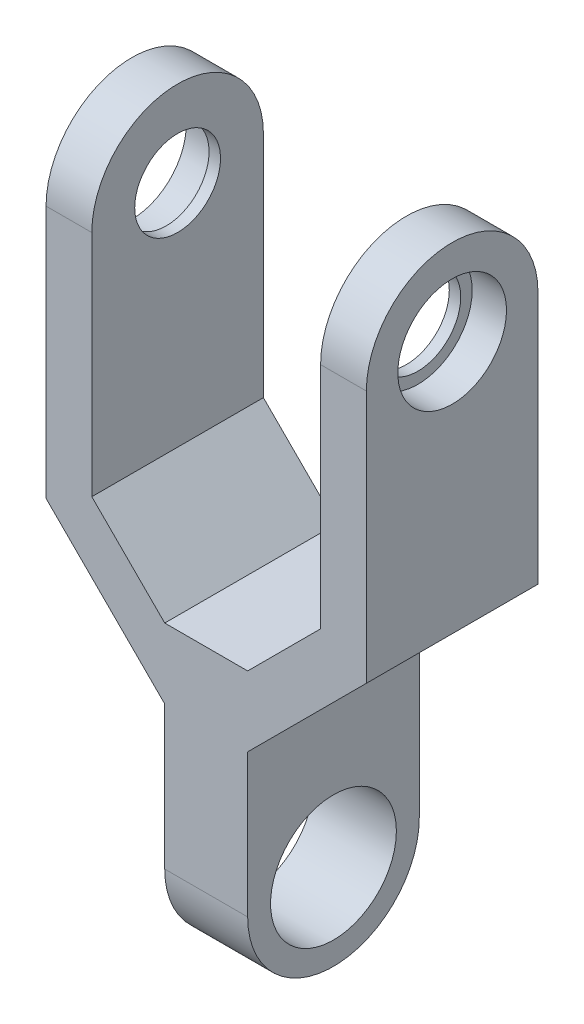
SolidWorks part; units mm, degrees
ref_plane "前视基准面" through (0, 0, 0) normal (0, 0, 1) x (1, 0, 0)
ref_plane "上视基准面" through (0, 0, 0) normal (0, 1, 0) x (1, 0, 0)
ref_plane "右视基准面" through (0, 0, 0) normal (1, 0, 0) x (0, 0, -1)
sketch "草图1" plane through (0, 0, 0) normal (0, 0, 1) x (1, 0, 0)
  line L0 (0, 0) -> (14.5, 0)
  line L1 (14.5, 0) -> (14.5, 25)
  line L2 (14.5, 25) -> (35.25, 45.75)
  line L3 (35.25, 45.75) -> (35.25, 90)
  line L4 (35.25, 90) -> (27.25, 90)
  line L5 (27.25, 90) -> (27.25, 50)
  line L6 (27.25, 50) -> (-12.75, 50)
  line L7 (-12.75, 50) -> (-12.75, 90)
  line L8 (-12.75, 90) -> (-20.75, 90)
  line L9 (-20.75, 90) -> (-20.75, 45.75)
  line L11 (0, 25) -> (0, 0)
  line L12 (0, 25) -> (-20.75, 45.75)
  line L13 (7.25, 0) -> (7.25, 35.1674) construction
  dimension "D1" = 135
  dimension "D2" = 135
  dimension "D3" = 14.5
  dimension "D4" = 8
  dimension "D5" = 8
  dimension "D6" = 40
  dimension "D7" = 90
  dimension "D8" = 25
  dimension "D9" = 40
extrude "凸台-拉伸1" add sketch "草图1" along normal blind 30
sketch "草图2" plane through (0, 0, 30) normal (0, 0, 1) x (1, 0, 0)
  line L0 (-12.75, 50) -> (0, 37.25)
  line L1 (0, 37.25) -> (14.5, 37.25)
  line L2 (14.5, 37.25) -> (27.25, 50)
  line L3 (-20.75, 45.75) -> (0, 25) construction
  line L4 (14.5, 25) -> (35.25, 45.75) construction
  line L5 (-12.75, 50) -> (27.25, 50)
extrude "切除-拉伸1" cut sketch "草图2" against normal through all
sketch "草图3" plane through (14.5, 0, 0) normal (1, 0, 0) x (0, 0, -1)
  line L0 (-30, 0) -> (0, 0)
  arc A0 (-30, 0) -> (0, 0) centre (-15, 0) ccw
extrude "凸台-拉伸2" add sketch "草图3" against normal up to surface (14.5 mm away) up to face at (0, 12.5, 15)
sketch "草图4" plane through (14.5, 0, 0) normal (1, 0, 0) x (0, 0, -1)
  circle A0 centre (-15, 0) radius 11
  dimension "D1" = 22
extrude "切除-拉伸2" cut sketch "草图4" against normal blind 20
sketch "草图5" plane through (14.5, 0, 0) normal (1, 0, 0) x (0, 0, -1)
  circle A0 centre (-15, 0) radius 9.5
  dimension "D1" = 19
extrude "切除-拉伸3" [suppressed] cut sketch "草图5" against normal blind 6
sketch "草图6" plane through (0, 0, 0) normal (-1, 0, 0) x (0, 0, 1)
  circle A0 centre (15, 0) radius 9.5
  dimension "D1" = 19
extrude "切除-拉伸4" [suppressed] cut sketch "草图6" against normal blind 6
sketch "草图7" plane through (35.25, 0, 0) normal (1, 0, 0) x (0, 0, -1)
  line L0 (-30, 90) -> (0, 90)
  arc A0 (-30, 90) -> (0, 90) centre (-15, 90) cw
extrude "凸台-拉伸3" add sketch "草图7" against normal up to surface (8 mm away) up to face at (27.25, 70, 15)
sketch "草图8" plane through (-20.75, 0, 0) normal (-1, 0, 0) x (0, 0, 1)
  line L0 (0, 90) -> (30, 90)
  arc A0 (0, 90) -> (30, 90) centre (15, 90) cw
extrude "凸台-拉伸4" add sketch "草图8" against normal up to surface (8 mm away) up to face at (-12.75, 70, 15)
sketch "草图9" plane through (-20.75, 0, 0) normal (-1, 0, 0) x (0, 0, 1)
  circle A0 centre (15, 90) radius 7.5
  dimension "D1" = 15
extrude "切除-拉伸5" cut sketch "草图9" against normal blind 62
sketch "草图10" plane through (-20.75, 0, 0) normal (-1, 0, 0) x (0, 0, 1)
  circle A0 centre (15, 90) radius 9.5
  dimension "D1" = 19
extrude "切除-拉伸6" cut sketch "草图10" against normal blind 6
sketch "草图11" plane through (35.25, 0, 0) normal (1, 0, 0) x (0, 0, -1)
  circle A0 centre (-15, 90) radius 9.5
  dimension "D1" = 19
extrude "切除-拉伸7" cut sketch "草图11" against normal blind 6
